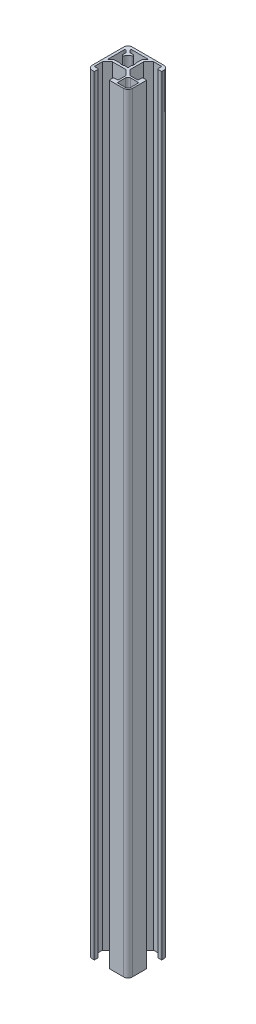
SolidWorks part; units mm, degrees
ref_plane "Ebene vorne" through (0, 0, 0) normal (0, 0, 1) x (1, 0, 0)
ref_plane "Ebene oben" through (0, 0, 0) normal (0, 1, 0) x (1, 0, 0)
ref_plane "Ebene rechts" through (0, 0, 0) normal (1, 0, 0) x (0, 0, -1)
ref_plane "Ebene1" through (0, 0, 0) normal (0, -1, 0) x (1, 0, 0)
sketch "Skizze1" plane through (0, 0, 0) normal (0, -1, 0) x (1, 0, 0)
  line L0 (3.45, 23) -> (2.5, 23)
  line L1 (0, 20.5) -> (0, 2.5)
  line L2 (2.5, 0) -> (20.5, 0)
  line L3 (23, 2.5) -> (23, 3.45)
  line L4 (22.7, 3.75) -> (21, 3.75)
  line L5 (20.5, 3.25) -> (20.5, 1.5)
  line L6 (20.2, 1.2) -> (15.8607, 1.2)
  line L7 (15.8607, 1.2) -> (13, 4.0607)
  line L8 (13, 4.0607) -> (13, 11.9393)
  line L9 (13, 11.9393) -> (15.8607, 14.8)
  line L10 (15.8607, 14.8) -> (20.2, 14.8)
  line L11 (20.5, 14.5) -> (20.5, 12.75)
  line L12 (21, 12.25) -> (22.7, 12.25)
  line L13 (23, 12.55) -> (23, 20.5)
  line L14 (20.5, 23) -> (12.55, 23)
  line L15 (12.25, 22.7) -> (12.25, 21)
  line L16 (12.75, 20.5) -> (14.5, 20.5)
  line L17 (14.8, 20.2) -> (14.8, 15.8607)
  line L18 (14.8, 15.8607) -> (11.9393, 13)
  line L19 (11.9393, 13) -> (4.0607, 13)
  line L20 (4.0607, 13) -> (1.2, 15.8607)
  line L21 (1.2, 15.8607) -> (1.2, 20.2)
  line L22 (1.5, 20.5) -> (3.25, 20.5)
  line L23 (3.75, 21) -> (3.75, 22.7)
  line L24 (1.5, 3.7678) -> (1.5, 12.7151)
  line L25 (2.0121, 12.9272) -> (3.1464, 11.7929)
  line L26 (3.8536, 11.5) -> (5.9142, 11.5)
  line L27 (5.9142, 11.5) -> (5.9949, 11.4193)
  line L28 (10.0051, 11.4193) -> (10.0858, 11.5)
  line L29 (10.0858, 11.5) -> (11, 11.5)
  line L30 (11.5, 11) -> (11.5, 10.0858)
  line L31 (11.5, 10.0858) -> (11.4193, 10.0051)
  line L32 (11.4193, 5.9949) -> (11.5, 5.9142)
  line L33 (11.5, 5.9142) -> (11.5, 3.8536)
  line L34 (11.7929, 3.1464) -> (12.9272, 2.0121)
  line L35 (12.7151, 1.5) -> (3.7678, 1.5)
  line L36 (3.4142, 2.3536) -> (4.4142, 3.3536)
  line L37 (4.7678, 3.5) -> (6.5639, 3.5)
  line L38 (3.5, 6.5639) -> (3.5, 4.7678)
  line L39 (3.3536, 4.4142) -> (2.3536, 3.4142)
  line L40 (15.8, 17.3) -> (15.8, 21.5)
  line L41 (16.3, 22) -> (20.5, 22)
  line L42 (22, 20.5) -> (22, 16.3)
  line L43 (21.5, 15.8) -> (17.3, 15.8)
  arc A0 (3.75, 22.7) -> (3.45, 23) centre (3.45, 22.7) ccw
  arc A1 (2.5, 23) -> (0, 20.5) centre (2.5, 20.5) ccw
  arc A2 (0, 2.5) -> (2.5, 0) centre (2.5, 2.5) ccw
  arc A3 (20.5, 0) -> (23, 2.5) centre (20.5, 2.5) ccw
  arc A4 (23, 3.45) -> (22.7, 3.75) centre (22.7, 3.45) ccw
  arc A5 (21, 3.75) -> (20.5, 3.25) centre (21, 3.25) ccw
  arc A6 (20.5, 1.5) -> (20.2, 1.2) centre (20.2, 1.5) cw
  arc A7 (20.2, 14.8) -> (20.5, 14.5) centre (20.2, 14.5) cw
  arc A8 (20.5, 12.75) -> (21, 12.25) centre (21, 12.75) ccw
  arc A9 (22.7, 12.25) -> (23, 12.55) centre (22.7, 12.55) ccw
  arc A10 (23, 20.5) -> (20.5, 23) centre (20.5, 20.5) ccw
  arc A11 (12.55, 23) -> (12.25, 22.7) centre (12.55, 22.7) ccw
  arc A12 (12.25, 21) -> (12.75, 20.5) centre (12.75, 21) ccw
  arc A13 (14.5, 20.5) -> (14.8, 20.2) centre (14.5, 20.2) cw
  arc A14 (1.2, 20.2) -> (1.5, 20.5) centre (1.5, 20.2) cw
  arc A15 (3.25, 20.5) -> (3.75, 21) centre (3.25, 21) ccw
  arc A16 (2.3536, 3.4142) -> (1.5, 3.7678) centre (2, 3.7678) cw
  arc A17 (1.5, 12.7151) -> (2.0121, 12.9272) centre (1.8, 12.7151) cw
  arc A18 (3.1464, 11.7929) -> (3.8536, 11.5) centre (3.8536, 12.5) ccw
  arc A19 (5.9949, 11.4193) -> (6.3398, 11.3625) centre (6.207, 11.6315) ccw
  arc A20 (6.3398, 11.3625) -> (9.6602, 11.3625) centre (8, 8) cw
  arc A21 (9.6602, 11.3625) -> (10.0051, 11.4193) centre (9.793, 11.6315) ccw
  arc A22 (11, 11.5) -> (11.5, 11) centre (11, 11) cw
  arc A23 (11.4193, 10.0051) -> (11.3625, 9.6602) centre (11.6315, 9.793) ccw
  arc A24 (11.3625, 9.6602) -> (11.3625, 6.3398) centre (8, 8) cw
  arc A25 (11.3625, 6.3398) -> (11.4193, 5.9949) centre (11.6315, 6.207) ccw
  arc A26 (11.5, 3.8536) -> (11.7929, 3.1464) centre (12.5, 3.8536) ccw
  arc A27 (12.9272, 2.0121) -> (12.7151, 1.5) centre (12.7151, 1.8) cw
  arc A28 (3.7678, 1.5) -> (3.4142, 2.3536) centre (3.7678, 2) cw
  arc A29 (4.4142, 3.3536) -> (4.7678, 3.5) centre (4.7678, 3) cw
  arc A30 (6.5639, 3.5) -> (6.7328, 4.4706) centre (6.5639, 4) ccw
  arc A31 (6.7328, 4.4706) -> (4.4706, 6.7328) centre (8, 8) cw
  arc A32 (4.4706, 6.7328) -> (3.5, 6.5639) centre (4, 6.5639) ccw
  arc A33 (3.5, 4.7678) -> (3.3536, 4.4142) centre (3, 4.7678) cw
  arc A34 (17.3, 15.8) -> (15.8, 17.3) centre (17.3, 17.3) cw
  arc A35 (15.8, 21.5) -> (16.3, 22) centre (16.3, 21.5) cw
  arc A36 (20.5, 22) -> (22, 20.5) centre (20.5, 20.5) cw
  arc A37 (22, 16.3) -> (21.5, 15.8) centre (21.5, 16.3) cw
extrude "Aufsatz-Linear austragen1" add sketch "Skizze1" against normal blind 440
